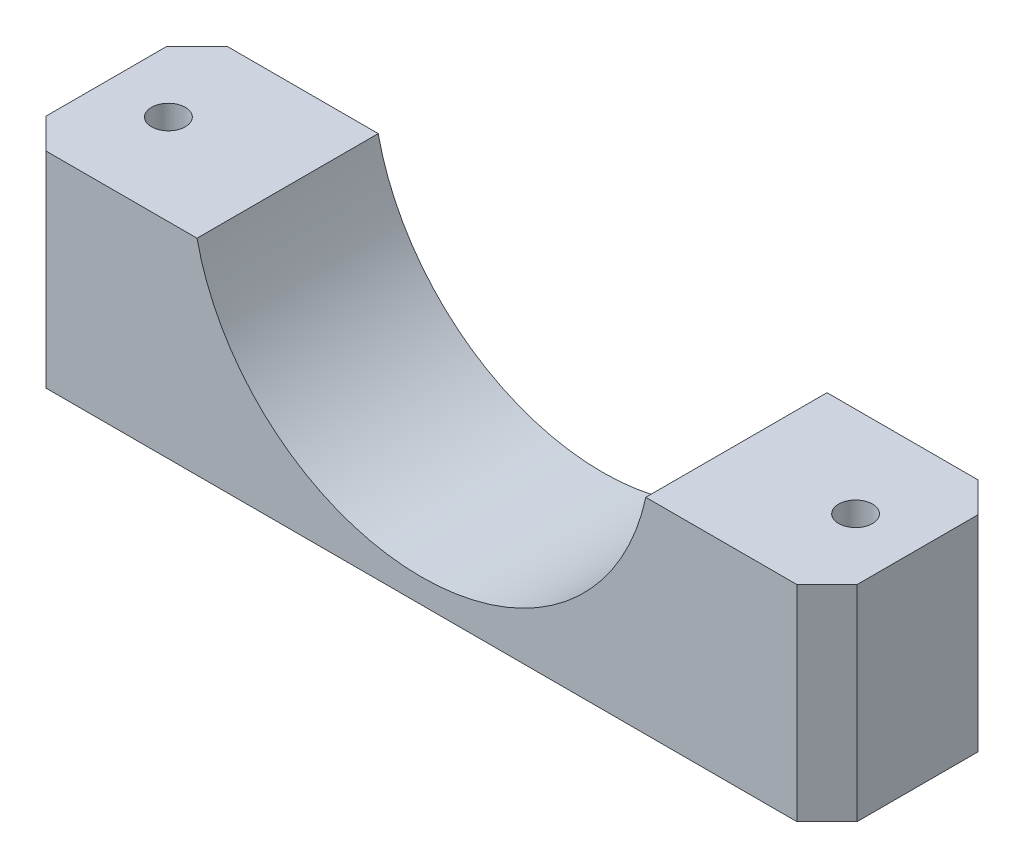
SolidWorks part; units mm, degrees
ref_plane "Front Plane" through (0, 0, 0) normal (0, 0, 1) x (1, 0, 0)
ref_plane "Top Plane" through (0, 0, 0) normal (0, 1, 0) x (1, 0, 0)
ref_plane "Right Plane" through (0, 0, 0) normal (1, 0, 0) x (0, 0, -1)
sketch "Sketch1" plane through (0, 0, 0) normal (0, 0, 1) x (1, 0, 0)
  line L0 (-18.5742, -4) -> (-33.5742, -4)
  line L1 (-33.5742, -4) -> (-33.5742, -21)
  line L2 (-33.5742, -21) -> (33.5742, -21)
  line L3 (33.5742, -21) -> (33.5742, -4)
  line L4 (33.5742, -4) -> (18.5742, -4)
  arc A0 (-18.5742, -4) -> (18.5742, -4) centre (0, 0) ccw
  dimension "D1" = 19
  dimension "D2" = 15
  dimension "D3" = 15
  dimension "D4" = 21
  dimension "D5" = 4
extrude "Boss-Extrude1" add sketch "Sketch1" along normal blind 15 contours L4 A0 L0 L1 L2 L3
chamfer "Chamfer1" distance 2.5 4 edges at (33.5742, -12.5, 0) (33.5742, -12.5, 15) (-33.5742, -12.5, 0) (-33.5742, -12.5, 15)
sketch "Sketch2" plane through (0, -4, 0) normal (0, 1, 0) x (1, 0, 0)
  line L0 (0, -8.25) -> (0, 8.25) construction
  circle A0 centre (28.4416, -7.5) radius 1.4
  circle A1 centre (-28.4416, -7.5) radius 1.4
  dimension "D1" = 2.8
extrude "Cut-Extrude1" cut sketch "Sketch2" against normal through all
